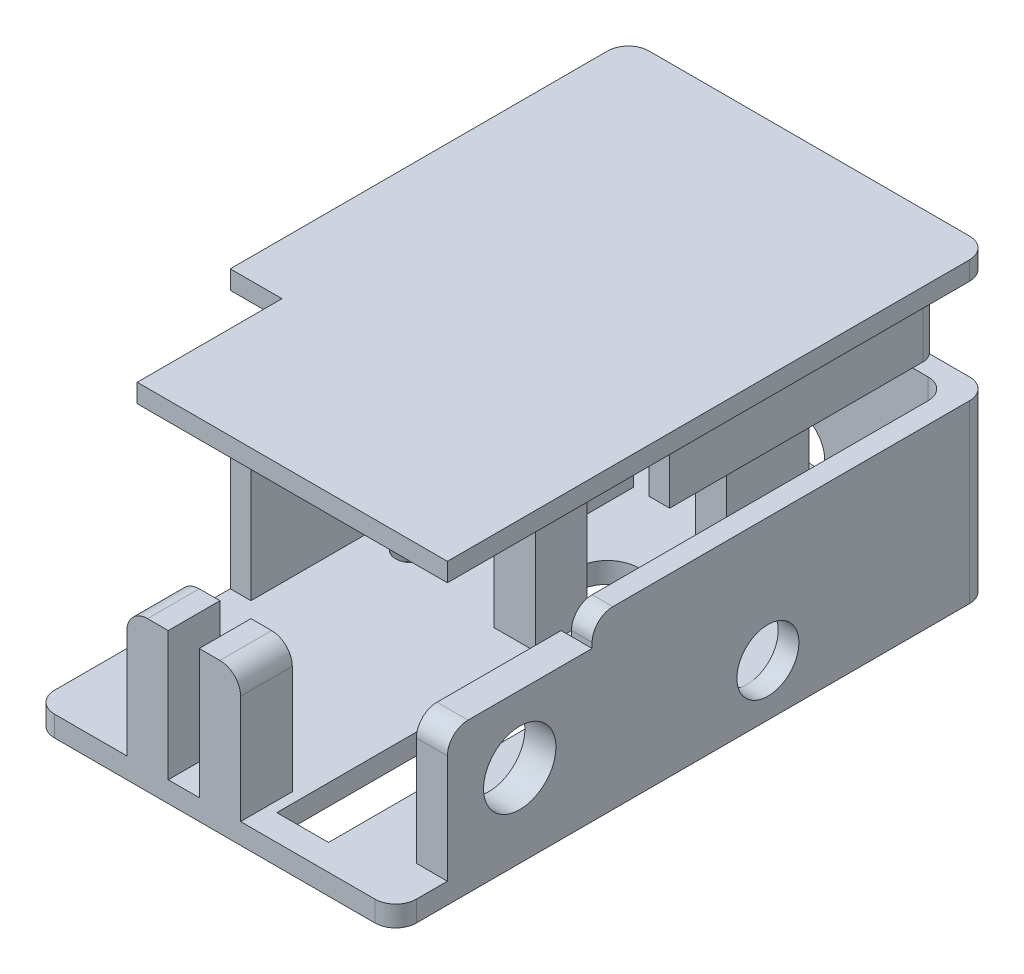
SolidWorks part; units mm, degrees
ref_plane "Front Plane" through (0, 0, 0) normal (0, 0, 1) x (1, 0, 0)
ref_plane "Top Plane" through (0, 0, 0) normal (0, 1, 0) x (1, 0, 0)
ref_plane "Right Plane" through (0, 0, 0) normal (1, 0, 0) x (0, 0, -1)
sketch "Sketch2" plane through (0, 0, 0) normal (0, 1, 0) x (1, 0, 0)
  line L0 (14, -28.5) -> (17, -28.5)
  line L1 (2, -28.5) -> (-2, -28.5)
  line L2 (2, -28.5) -> (2, -33.5)
  line L3 (2, -33.5) -> (-2, -33.5)
  line L4 (-2, -28.5) -> (-2, -33.5)
  line L5 (2, -28.5) -> (-2, -33.5) construction
  line L6 (2, -33.5) -> (-2, -28.5) construction
  line L7 (14, -28.5) -> (14, -14.5)
  line L8 (-2, -5) -> (2, -5)
  line L9 (-2, -5) -> (-2, 0)
  line L10 (-2, 0) -> (2, 0)
  line L11 (2, -5) -> (2, 0)
  line L12 (-2, -5) -> (2, 0) construction
  line L13 (-2, 0) -> (2, -5) construction
  line L14 (14, -14.5) -> (17, -14.5)
  line L15 (17, -28.5) -> (17, -14.5)
  line L16 (14, -28.5) -> (17, -14.5) construction
  line L17 (14, -14.5) -> (17, -28.5) construction
  line L19 (-9, -28.5) -> (-5, -28.5)
  line L20 (-9, -28.5) -> (-9, -33.5)
  line L21 (-9, -33.5) -> (-5, -33.5)
  line L22 (-5, -28.5) -> (-5, -33.5)
  line L23 (-9, -28.5) -> (-5, -33.5) construction
  line L24 (-9, -33.5) -> (-5, -28.5) construction
  point P4 (0, -31)
  point P6 (0, 0)
  point P11 (0, -2.5)
  point P16 (15.5, -21.5)
  point P21 (-7, -31)
  dimension "D1" = 23.5
  dimension "D2" = 5
  dimension "D3" = 5
  dimension "D4" = 4
  dimension "D5" = 14
  dimension "D6" = 3
  dimension "D7" = 16
  dimension "D8" = 12
  dimension "D9" = 4
  dimension "D10" = 3
extrude "Boss-Extrude2" add sketch "Sketch2" along normal blind 12.5
sketch "Sketch3" plane through (0, 0, 0) normal (0, -1, 0) x (1, 0, 0)
  line L1 (-18, 33.5) -> (17, 33.5)
  line L2 (-18, 33.5) -> (-18, -24)
  line L3 (-18, -24) -> (17, -24)
  line L4 (17, 33.5) -> (17, -24)
  line L5 (17, 28.5) -> (17, 14.5) construction
  line L6 (-2, 33.5) -> (2, 33.5) construction
  dimension "D1" = 24
  dimension "D2" = 16
  dimension "D3" = 0
extrude "Boss-Extrude3" add sketch "Sketch3" along normal blind 2
sketch "Sketch4" plane through (0, 0, 0) normal (1, 0, 0) x (0, 0, -1)
  line L4 (-28.5, 12.5) -> (-14.5, 12.5) construction
  circle A2 centre (-21.5, 6) radius 3.5
  point P19 (-21.5, 12.5)
  dimension "D3" = 7
  dimension "D5" = 6
extrude "Cut-Extrude1" cut sketch "Sketch4" against normal through all both and the other way through all
sketch "Sketch5" plane through (-2, 0, 0) normal (-1, 0, 0) x (0, 0, 1)
  line L1 (0, 12.5) -> (5, 12.5) construction
  circle A0 centre (2.5, 6.5) radius 0.6
  point P13 (2.5, 12.5)
  dimension "D1" = 1.2
  dimension "D2" = 6.5
extrude "Boss-Extrude4" add sketch "Sketch5" along normal blind 1.5
sketch "Sketch6" plane through (0, 0, 0) normal (0, 1, 0) x (1, 0, 0)
  line L0 (10, 0) -> (-10, 0) construction
  line L1 (-10, 13.5) -> (-7, 13.5)
  line L2 (-10, 13.5) -> (-10, 5.5)
  line L3 (-10, 5.5) -> (-7, 5.5)
  line L4 (-7, 13.5) -> (-7, 5.5)
  line L5 (-10, 13.5) -> (-7, 5.5) construction
  line L6 (-10, 5.5) -> (-7, 13.5) construction
  line L7 (0, -55) -> (0, 55) construction
  line L8 (10, 5.5) -> (7, 13.5) construction
  line L9 (10, 13.5) -> (7, 5.5) construction
  line L10 (7, 13.5) -> (7, 5.5)
  line L11 (10, 5.5) -> (7, 5.5)
  line L12 (10, 13.5) -> (10, 5.5)
  line L13 (10, 13.5) -> (7, 13.5)
  point P4 (-8.5, 9.5)
  point P9 (0, 0)
  point P17 (8.5, 9.5)
  dimension "D1" = 8
  dimension "D2" = 3
  dimension "D3" = 20
  dimension "D4" = 5.5
extrude "Boss-Extrude5" add sketch "Sketch6" along normal up to surface (12.5 mm away) up to face at (0, 12.5, 2.5)
sketch "Sketch14" plane through (0, 12.5, 0) normal (0, 1, 0) x (1, 0, 0)
  line L0 (-7, 5.5) -> (-10, 5.5) construction
  line L1 (-10, 13.5) -> (-9, 13.5)
  line L2 (-10, 13.5) -> (-10, 5.5)
  line L3 (-10, 5.5) -> (-9, 5.5)
  line L4 (-9, 13.5) -> (-9, 5.5)
  line L5 (-10, 13.5) -> (-9, 5.5) construction
  line L6 (-10, 5.5) -> (-9, 13.5) construction
  line L7 (0, -55) -> (0, 55) construction
  line L8 (10, 5.5) -> (9, 13.5) construction
  line L9 (10, 13.5) -> (9, 5.5) construction
  line L10 (9, 13.5) -> (9, 5.5)
  line L11 (10, 5.5) -> (9, 5.5)
  line L12 (10, 13.5) -> (10, 5.5)
  line L13 (10, 13.5) -> (9, 13.5)
  point P4 (-9.5, 9.5)
  point P14 (9.5, 9.5)
  dimension "D1" = 1
extrude "Boss-Extrude7" add sketch "Sketch14" along normal blind 2
sketch "Sketch9" plane through (0, 0, 0) normal (0, 1, 0) x (1, 0, 0)
  line L0 (-18, 24) -> (17, 24)
  line L1 (17, 24) -> (17, -14.5)
  line L2 (17, 24) -> (17, -14.5) construction
  line L3 (17, -14.5) -> (15, -14.5)
  line L4 (15, -14.5) -> (15, 22)
  line L5 (15, 22) -> (-16, 22)
  line L6 (-16, 22) -> (-16, -14.5)
  line L7 (-16, -14.5) -> (-18, -14.5)
  line L8 (-18, -33.5) -> (-18, 24) construction
  line L9 (-18, -14.5) -> (-18, 24)
  dimension "D1" = 2
  dimension "D2" = 2
  dimension "D3" = 2
extrude "Boss-Extrude8" add sketch "Sketch9" along normal blind 15
sketch "Sketch10" plane through (0, 0, -24) normal (0, 1, 0) x (-1, 0, 0)
  line L0 (-17, 0) -> (18, 0) construction
  circle A2 centre (0, 20) radius 3
  dimension "D2" = 20
  dimension "D1" = 6
extrude "Cut-Extrude3" cut sketch "Sketch10" against normal up to next
sketch "Sketch12" plane through (0, 0, 0) normal (0, 1, 0) x (1, 0, 0)
  line L0 (12.5, -2.5) -> (-12.5, -2.5) construction
  line L1 (0, -9.35) -> (0, 9.35) construction
  line L2 (-2, 0) -> (-2, -5) construction
  circle A0 centre (-12.5, -2.5) radius 1.5
  circle A1 centre (12.5, -2.5) radius 1.5
  point P5 (0, -2.5)
  point P8 (-2, -2.5)
  dimension "D1" = 3
  dimension "D2" = 25
extrude "Cut-Extrude4" cut sketch "Sketch12" against normal through all both and the other way through all
sketch "Sketch15" plane through (0, 0, 0) normal (0, 1, 0) x (1, 0, 0)
  line L1 (3, -2.5) -> (8, -2.5)
  line L2 (3, -2.5) -> (3, -31)
  line L3 (3, -31) -> (8, -31)
  line L4 (8, -2.5) -> (8, -31)
  line L5 (3, -2.5) -> (8, -31) construction
  line L6 (3, -31) -> (8, -2.5) construction
  line L7 (2, -33.5) -> (2, -28.5) construction
  line L10 (2, -5) -> (2, 0) construction
  point P4 (5.5, -16.75)
  point P5 (2, -31)
  point P12 (2, -2.5)
  dimension "D2" = 1
  dimension "D3" = 5
extrude "Cut-Extrude5" cut sketch "Sketch15" against normal through all both and the other way through all
sketch "Sketch17" plane through (0, 0, -24) normal (0, 0, -1) x (-1, 0, 0)
  line L0 (-7, 12.5) -> (-9, 12.5) construction
  line L1 (-5, 12.5) -> (5, 12.5)
  line L2 (-5, 12.5) -> (-5, 17.5)
  line L3 (-5, 17.5) -> (5, 17.5)
  line L4 (5, 12.5) -> (5, 17.5)
  line L5 (-5, 12.5) -> (5, 17.5) construction
  line L6 (-5, 17.5) -> (5, 12.5) construction
  point P4 (0, 15)
  dimension "D1" = 10
  dimension "D2" = 5
extrude "Cut-Extrude7" cut sketch "Sketch17" against normal up to next
fillet "Fillet1" radius 2 13 edges at (15.5, 12.5, 28.5) (16, 15, 14.5) (5, 15, -23) (-5, 15, -23) (-17, 15, 14.5) (-18, -1, 33.5) (-18, 6.5, -24) (17, 6.5, -24) (15, 7.5, -22) (-16, 7.5, -22) (2, 12.5, 31) (-9, 12.5, 31) (17, -1, 33.5)
sketch "Sketch18" plane through (17, 0, 0) normal (1, 0, 0) x (0, 0, -1)
  line L1 (5.5, 14.5) -> (5.5, 0) construction
  line L2 (-31, 0) -> (-2.5, 0) construction
  circle A0 centre (2.5, 3) radius 3
  dimension "D1" = 6
extrude "Cut-Extrude8" cut sketch "Sketch18" against normal up to next and the other way through all
mirror "Mirror1" about plane through (0, 0, 0) normal (1, 0, 0) of "Cut-Extrude8"
sketch "Sketch19" plane through (0, 0, -24) normal (0, 0, -1) x (-1, 0, 0)
  line L5 (-8, 0) -> (-3, 0) construction
  circle A0 centre (0, 3) radius 3
  dimension "D1" = 6
extrude "Cut-Extrude9" cut sketch "Sketch19" against normal up to next
ref_plane "Plane1" through (0, 25, 0) normal (0, 1, 0) x (1, 0, 0)
sketch "Sketch22" plane through (0, 25, 0) normal (0, 1, 0) x (1, 0, 0)
  line L0 (-14, 21.5) -> (-13.5, 21.5)
  line L1 (-13.5, 21.5) -> (-13.5, -4.5)
  line L6 (-15.5, 20) -> (-15.5, -4.5)
  line L7 (-15.5, -4.5) -> (-13.5, -4.5)
  line L9 (12.5, -4.5) -> (14.5, -4.5)
  line L13 (13, 21.5) -> (12.5, 21.5)
  line L14 (12.5, 21.5) -> (12.5, -4.5)
  line L16 (14.5, -4.5) -> (14.5, 20)
  arc A2 (14.5, 20) -> (13, 21.5) centre (13, 20) ccw
  arc A3 (-14, 21.5) -> (-15.5, 20) centre (-14, 20) ccw
  arc A4 (-14, 21.5) -> (-15.5, 20) centre (-14, 20) ccw
  arc A5 (14.5, 20) -> (13, 21.5) centre (13, 20) ccw
  dimension "D4" = 2
  dimension "D6" = 0.5
  dimension "D7" = 2
  dimension "D1" = 0.5
  dimension "D9" = 0.5
extrude "Boss-Extrude10" add sketch "Sketch22" against normal blind 7 separate body
sketch "Sketch21" plane through (0, 25, 0) normal (0, 1, 0) x (1, 0, 0)
  line L0 (-18, -12.5) -> (-18, -14.5)
  line L2 (-18, -14.5) -> (-13, -14.5)
  line L3 (-13, -14.5) -> (-13, -28.5)
  line L4 (-13, -28.5) -> (17, -28.5)
  line L5 (0, -28.5) -> (-2, -28.5) construction
  line L39 (17, -28.5) -> (17, -12.5)
  line L42 (17, -12.5) -> (17, 22)
  line L43 (15, 24) -> (7, 24)
  line L44 (7, 24) -> (5, 24)
  line L45 (5, 24) -> (-5, 24)
  line L46 (-5, 24) -> (-7, 24)
  line L47 (-18, 22) -> (-18, -12.5)
  line L48 (-7, 24) -> (-16, 24)
  line L49 (17, -12.5) -> (17, 22)
  line L50 (15, 24) -> (7, 24)
  line L51 (7, 24) -> (5, 24)
  line L52 (5, 24) -> (-5, 24)
  line L53 (-5, 24) -> (-7, 24)
  line L54 (-18, 22) -> (-18, -12.5)
  line L55 (-7, 24) -> (-16, 24)
  arc A12 (17, 22) -> (15, 24) centre (15, 22) ccw
  arc A13 (-16, 24) -> (-18, 22) centre (-16, 22) ccw
  arc A14 (17, 22) -> (15, 24) centre (15, 22) ccw
  arc A15 (-16, 24) -> (-18, 22) centre (-16, 22) ccw
  dimension "D2" = 5
  dimension "D1" = 0
extrude "Boss-Extrude9" add sketch "Sketch21" along normal blind 1.8
